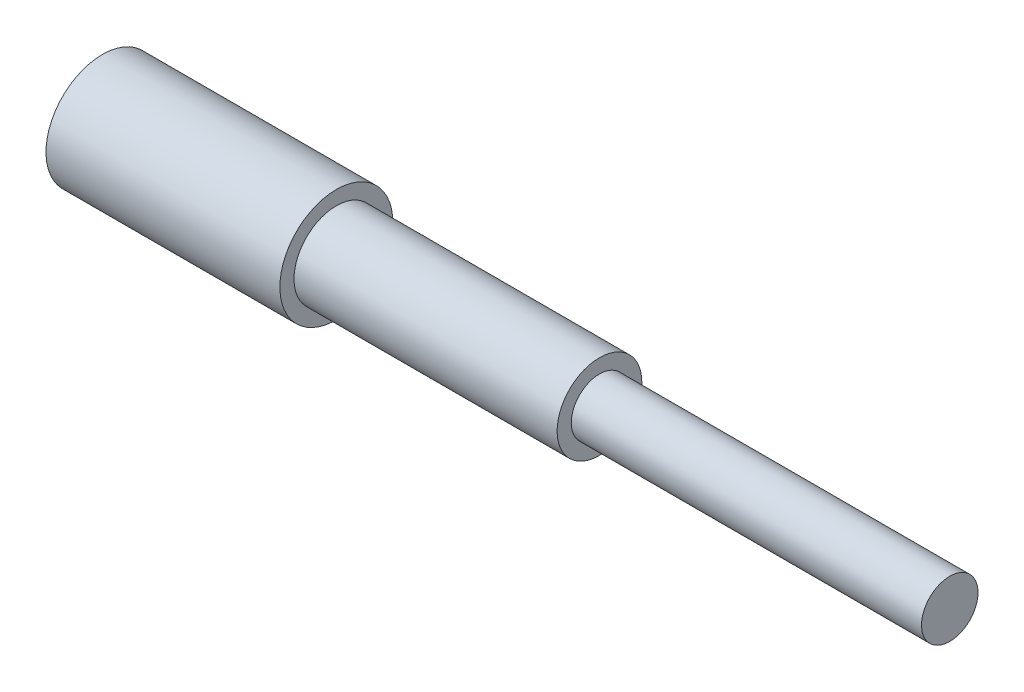
SolidWorks part; units mm, degrees
ref_plane "Ön Düzlem" through (0, 0, 0) normal (0, 0, 1) x (1, 0, 0)
ref_plane "Üst Düzlem" through (0, 0, 0) normal (0, 1, 0) x (1, 0, 0)
ref_plane "Sağ Düzlem" through (0, 0, 0) normal (1, 0, 0) x (0, 0, -1)
sketch "Çizim1" plane through (0, 0, 0) normal (0, 0, 1) x (1, 0, 0)
  line L0 (-124.6998, 0) -> (-124.6998, 20)
  line L1 (-124.6998, 20) -> (-41.8883, 20)
  line L2 (-41.8883, 20) -> (-41.8883, 15)
  line L3 (-41.8883, 15) -> (51.2747, 15)
  line L4 (51.2747, 15) -> (51.2747, 10)
  line L5 (51.2747, 10) -> (175.3002, 10)
  line L6 (175.3002, 10) -> (175.3002, 0)
  line L7 (175.3002, 0) -> (-124.6998, 0)
  dimension "D1" = 20
  dimension "D2" = 15
  dimension "D3" = 10
  dimension "D4" = 300
revolve "Döndür1" add sketch "Çizim1" angle 360 about L7
cosmetic thread "Kozmetik Diş Açma2"
